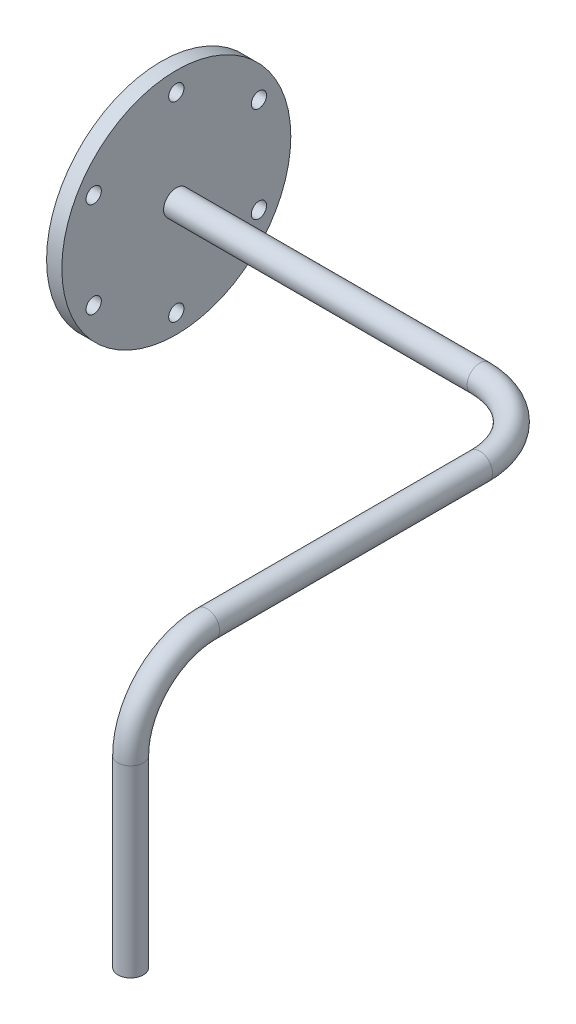
SolidWorks part; units mm, degrees
ref_plane "Front Plane" through (0, 0, 0) normal (0, 0, 1) x (1, 0, 0)
ref_plane "Top Plane" through (0, 0, 0) normal (0, 1, 0) x (1, 0, 0)
ref_plane "Right Plane" through (0, 0, 0) normal (1, 0, 0) x (0, 0, -1)
sketch "Sketch1" plane through (0, 0, 0) normal (1, 0, 0) x (0, 0, -1)
  line L0 (0, 0) -> (0, 72.19)
  line L1 (30, 102.19) -> (137.24, 102.19)
  arc A0 (0, 72.19) -> (30, 102.19) centre (30, 72.19) cw
  point P6 (0, 102.19)
  dimension "D3" = 30
  dimension "D1" = 102.19
  dimension "D2" = 137.24
sweep "Sweep4" add path "Sketch1" circular profile diameter 10 parameters "D3"=10
ref_plane "Plane3" through (0, 102.19, 0) normal (0, -1, 0) x (-1, 0, 0)
sketch "Sketch18" plane through (0, 102.19, 0) normal (0, -1, 0) x (-1, 0, 0)
  line L2 (30, 167.24) -> (155.29, 167.24)
  line L3 (5, 137.24) -> (-5, 137.24) construction
  line L4 (-5, 137.24) -> (5, 137.24)
  line L5 (5, 30) -> (5, 137.24) construction
  arc A0 (30, 167.24) -> (0, 137.24) centre (30, 137.24) ccw
  dimension "D2" = 30
  dimension "D1" = 155.29
  dimension "D3" = 10
sweep "Sweep6" add path "Sketch18" circular profile diameter 10 parameters "D3"=10
sketch "Sketch23" plane through (-30, 0, 0) normal (-1, 0, 0) x (0, 0, 1)
  circle A1 centre (-167.24, 102.19) radius 5
  circle A2 centre (-167.24, 102.19) radius 5
  dimension "D1" = 0
extrude "Boss-Extrude1" add sketch "Sketch23" along normal blind 119.29
shell "Shell1" thickness 2
sketch "Sketch25" plane through (0, 0, 0) normal (0, -1, 0) x (1, 0, 0)
  circle A0 centre (0, 0) radius 3
  dimension "D1" = 6
extrude "Cut-Extrude1" cut sketch "Sketch25" against normal blind 3.29
sketch "Sketch26" plane through (-149.29, 0, 0) normal (-1, 0, 0) x (0, 0, 1)
  circle A0 centre (-167.24, 102.19) radius 45
  dimension "D2" = 90
extrude "Boss-Extrude2" add sketch "Sketch26" along normal blind 6 separate body
sketch "Sketch27" plane through (-155.29, 0, 0) normal (-1, 0, 0) x (0, 0, 1)
  circle A0 centre (-167.24, 102.19) radius 37.5 construction
  circle A2 centre (-167.24, 102.19) radius 3
  circle A4 centre (-167.24, 139.69) radius 3
  dimension "D1" = 75
  dimension "D3" = 6
  dimension "D4" = 6
extrude "Cut-Extrude2" cut sketch "Sketch27" against normal blind 8
pattern_circular "CirPattern1" count 6 over 360 about axis through (0, 102.19, -167.24) along (1, 0, 0) of "Cut-Extrude2"
